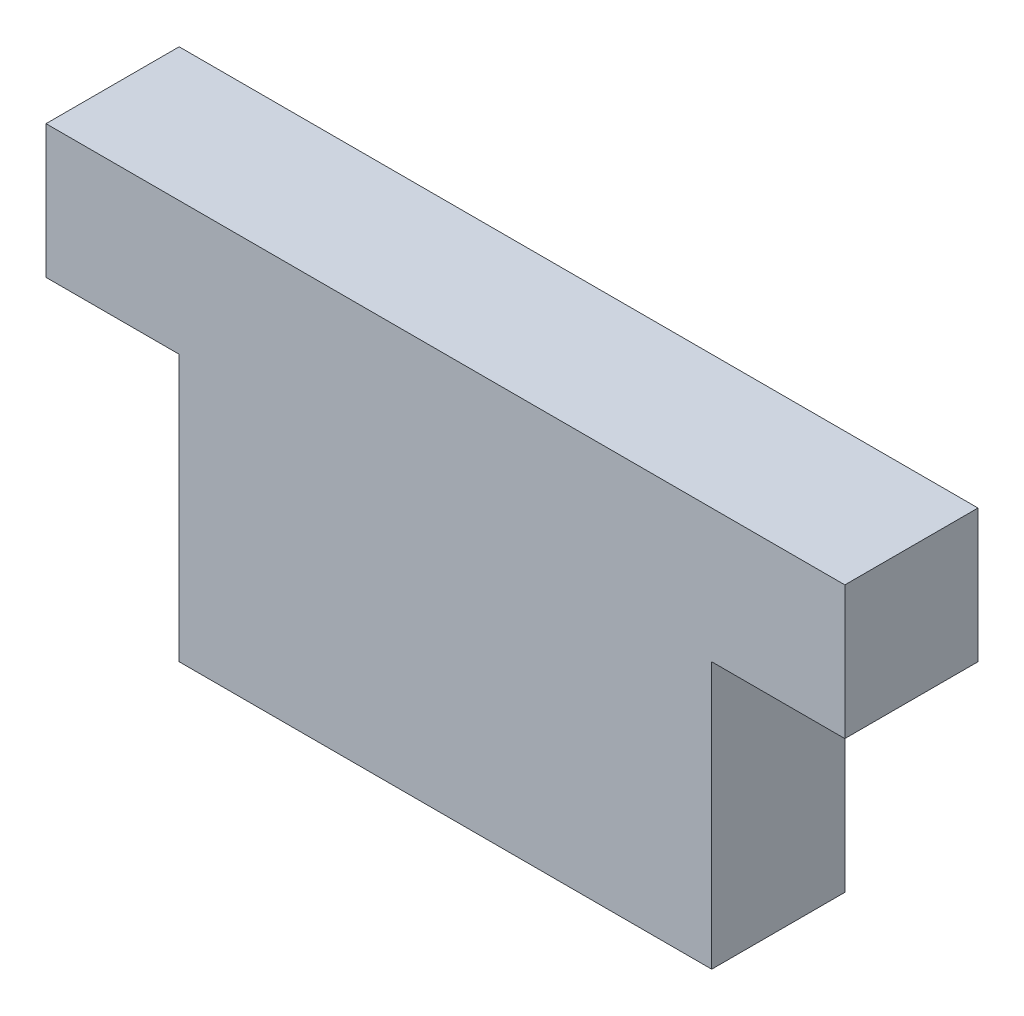
SolidWorks part; units mm, degrees
ref_plane "Front Plane" through (0, 0, 0) normal (0, 0, 1) x (1, 0, 0)
ref_plane "Top Plane" through (0, 0, 0) normal (0, 1, 0) x (1, 0, 0)
ref_plane "Right Plane" through (0, 0, 0) normal (1, 0, 0) x (0, 0, -1)
sketch "Sketch1" plane through (0, 0, 0) normal (0, 0, 1) x (1, 0, 0)
  line L1 (0, 0) -> (-20, 0)
  line L2 (0, 0) -> (0, -10)
  line L3 (0, -10) -> (-20, -10)
  line L4 (-20, 0) -> (-20, -10)
  line L5 (-25, 0) -> (5, 0)
  line L6 (-25, 0) -> (-25, 5)
  line L7 (-25, 5) -> (5, 5)
  line L8 (5, 0) -> (5, 5)
  dimension "D1" = 10
  dimension "D2" = 20
  dimension "D3" = 30
  dimension "D4" = 5
  dimension "D5" = 5
extrude "Boss-Extrude1" add sketch "Sketch1" along normal blind 5 contours L1 L4 L3 L2 | L5 L8 L7 L6 L1
